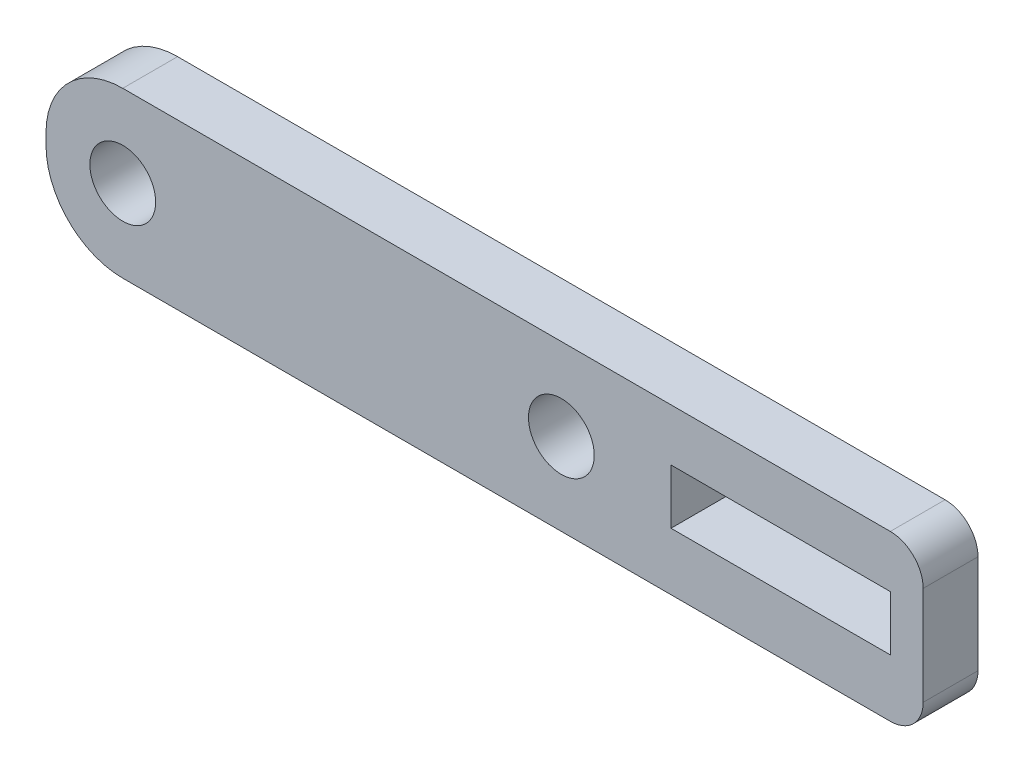
SolidWorks part; units mm, degrees
ref_plane "Front Plane" through (0, 0, 0) normal (0, 0, 1) x (1, 0, 0)
ref_plane "Top Plane" through (0, 0, 0) normal (0, 1, 0) x (1, 0, 0)
ref_plane "Right Plane" through (0, 0, 0) normal (1, 0, 0) x (0, 0, -1)
sketch "Sketch1" plane through (0, 0, 0) normal (0, 0, 1) x (1, 0, 0)
  line L0 (7, 7) -> (7, 8)
  line L1 (7, 0) -> (77, 0)
  line L2 (0, 7) -> (0, 8)
  line L3 (7, 15) -> (77, 15)
  line L4 (80, 12) -> (80, 3)
  line L5 (7, 7.5) -> (47, 7.5)
  line L7 (77, 10.25) -> (57, 10.25)
  line L8 (77, 10.25) -> (77, 5.25)
  line L9 (77, 5.25) -> (57, 5.25)
  line L10 (57, 10.25) -> (57, 5.25)
  arc A0 (0, 8) -> (7, 15) centre (7, 8) cw
  arc A1 (7, 0) -> (0, 7) centre (7, 7) cw
  circle A2 centre (7, 7.5) radius 3
  circle A3 centre (47, 7.5) radius 3
  arc A4 (77, 0) -> (80, 3) centre (77, 3) ccw
  arc A5 (80, 12) -> (77, 15) centre (77, 12) ccw
  point P7 (0, 15)
  point P10 (0, 0)
  dimension "D3" = 7
  dimension "D4" = 6
  dimension "D6" = 6
  dimension "D7" = 80
  dimension "D9" = 3
  dimension "D12" = 3
  dimension "D2" = 15
  dimension "D5" = 40
  dimension "D8" = 5
  dimension "D10" = 20
  dimension "D11" = 5.25
extrude "Boss-Extrude1" add sketch "Sketch1" along normal blind 5
